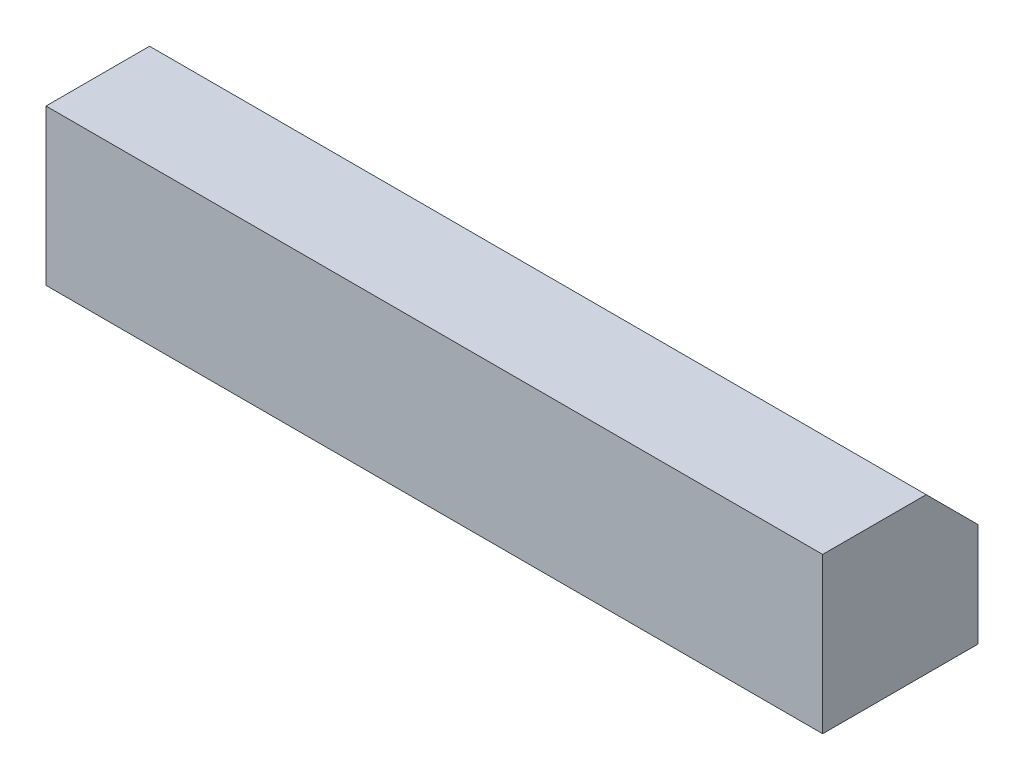
SolidWorks part; units mm, degrees
ref_plane "Спереди" through (0, 0, 0) normal (0, 0, 1) x (1, 0, 0)
ref_plane "Сверху" through (0, 0, 0) normal (0, 1, 0) x (1, 0, 0)
ref_plane "Справа" through (0, 0, 0) normal (1, 0, 0) x (0, 0, -1)
sketch "Эскиз1" plane through (0, 0, 0) normal (0, 1, 0) x (1, 0, 0)
  line L1 (-7.5, 1.5) -> (7.5, 1.5)
  line L2 (-7.5, 1.5) -> (-7.5, -1.5)
  line L3 (-7.5, -1.5) -> (7.5, -1.5)
  line L4 (7.5, 1.5) -> (7.5, -1.5)
  line L5 (-7.5, 1.5) -> (7.5, -1.5) construction
  line L6 (-7.5, -1.5) -> (7.5, 1.5) construction
  point P0 (0, 0)
  dimension "D1" = 15
  dimension "D2" = 3
extrude "Бобышка-Вытянуть1" add sketch "Эскиз1" along normal blind 3
chamfer "Фаска1" distance 1 angle 45 1 edges at (0, 3, -1.5)
